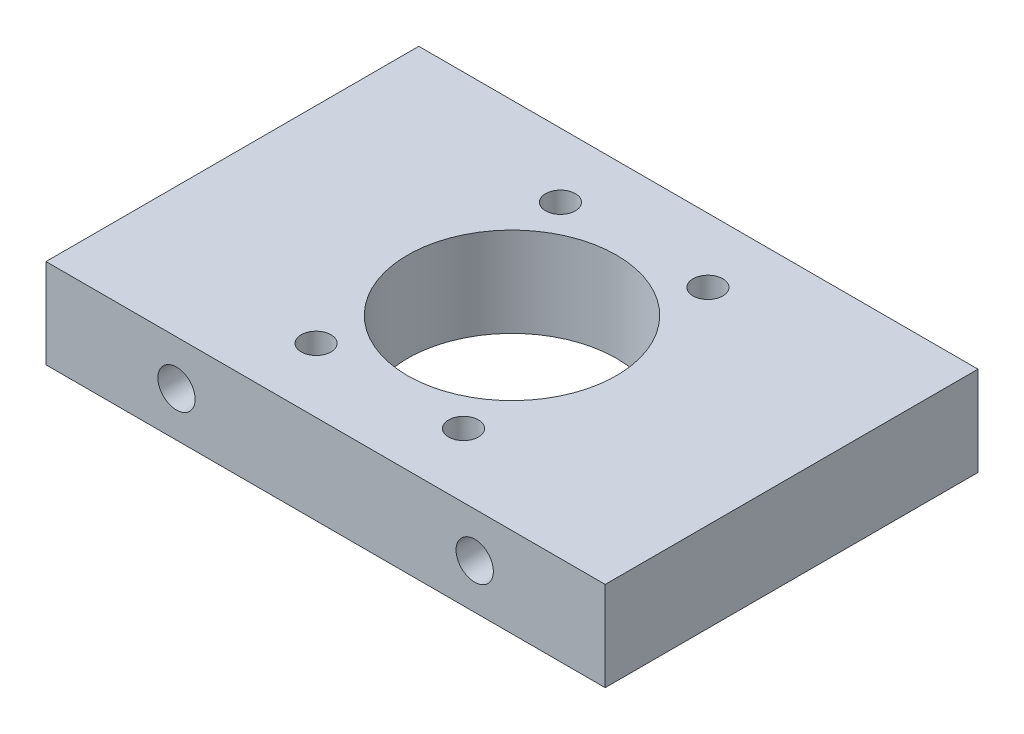
SolidWorks part; units mm, degrees
material "Acrylic (Medium-high impact)"
ref_plane "Front Plane" through (0, 0, 0) normal (0, 0, 1) x (1, 0, 0)
ref_plane "Top Plane" through (0, 0, 0) normal (0, 1, 0) x (1, 0, 0)
ref_plane "Right Plane" through (0, 0, 0) normal (1, 0, 0) x (0, 0, -1)
sketch "Sketch1" plane through (0, 0, 0) normal (0, 1, 0) x (1, 0, 0)
  line L1 (37.5, -25) -> (-37.5, -25)
  line L2 (37.5, -25) -> (37.5, 25)
  line L3 (37.5, 25) -> (-37.5, 25)
  line L4 (-37.5, -25) -> (-37.5, 25)
  line L5 (37.5, -25) -> (-37.5, 25) construction
  line L6 (37.5, 25) -> (-37.5, -25) construction
  point P0 (0, 0)
  dimension "D1" = 75
  dimension "D2" = 50
extrude "Boss-Extrude1" add sketch "Sketch1" along normal blind 12
sketch "Sketch2" plane through (0, 12, 0) normal (0, 1, 0) x (1, 0, 0)
  circle A0 centre (0, 0) radius 14.01
  dimension "D1" = 28.02
extrude "Cut-Extrude1" cut sketch "Sketch2" against normal blind 12
sketch "Sketch6" plane through (0, 0, -25) normal (0, 0, -1) x (-1, 0, 0)
  line L0 (37.5, 6) -> (-37.5, 6) construction
  line L1 (37.5, 12) -> (37.5, 0) construction
  line L2 (-37.5, 12) -> (-37.5, 0) construction
sketch "Sketch9" plane through (0, 0, 0) normal (0, -1, 0) x (1, 0, 0)
  line L0 (-37.5, 16.3888) -> (37.5, 16.3888) construction
  line L1 (-37.5, -25) -> (-37.5, 25) construction
  line L2 (37.5, 25) -> (37.5, -25) construction
  line L3 (-37.5, 0) -> (27.9544, 0) construction
  line L4 (0, 0) -> (0, 21.7355) construction
  circle A0 centre (-9.887, 16.3888) radius 2
  circle A1 centre (9.887, 16.3888) radius 2
  circle A2 centre (-9.887, -16.3888) radius 2
  circle A3 centre (9.887, -16.3888) radius 2
  dimension "D1" = 4
extrude "Cut-Extrude2" cut sketch "Sketch9" against normal blind 19
cosmetic thread "Cosmetic Thread3" parameters "D2"=5
cosmetic thread "Cosmetic Thread4" parameters "D2"=5
cosmetic thread "Cosmetic Thread5" parameters "D2"=5
cosmetic thread "Cosmetic Thread6" parameters "D2"=5
sketch "Sketch10" plane through (0, 0, -25) normal (0, 0, -1) x (-1, 0, 0)
  line L4 (-37.5, 0) -> (37.5, 0)
  line L5 (37.5, 0) -> (37.5, 12)
  line L6 (37.5, 12) -> (-37.5, 12)
  line L7 (-37.5, 12) -> (-37.5, 0)
  line L8 (-37.5, 0) -> (37.5, 0)
  line L9 (37.5, 0) -> (37.5, 12)
  line L10 (37.5, 12) -> (-37.5, 12)
  line L11 (-37.5, 12) -> (-37.5, 0)
  circle A0 centre (-20, 6) radius 3
  dimension "D1" = 0
hole_wizard "Ø5.0mm Dowel Hole1" positions "Sketch12" profile "Sketch11" hole size "Ø5.0" standard "ISO"
sketch "Sketch12" plane through (0, 0, -25) normal (0, 0, -1) x (-1, 0, 0)
  point P0 (-20, 6)
sketch "Sketch11" plane through (20, 6, -25) normal (1, 0, 0) x (0, 1, 0)
  line L0 (0, 0) -> (0, 51.5022)
  line L1 (0, 51.5022) -> (2.5, 50)
  line L2 (2.5, 50) -> (2.5, 0)
  line L5 (2.5, 0) -> (0, 0)
  line L10 (0, 51.5022) -> (-2.5, 50) construction
  line L11 (0, -6.35) -> (0, 107.95) construction
  dimension "Hole Dia." = 5
  dimension "Hole Depth" = 50
  dimension "Drill Angle" = 118
mirror "Mirror1" about plane through (0, 0, 0) normal (1, 0, 0) of "Ø5.0mm Dowel Hole1"
